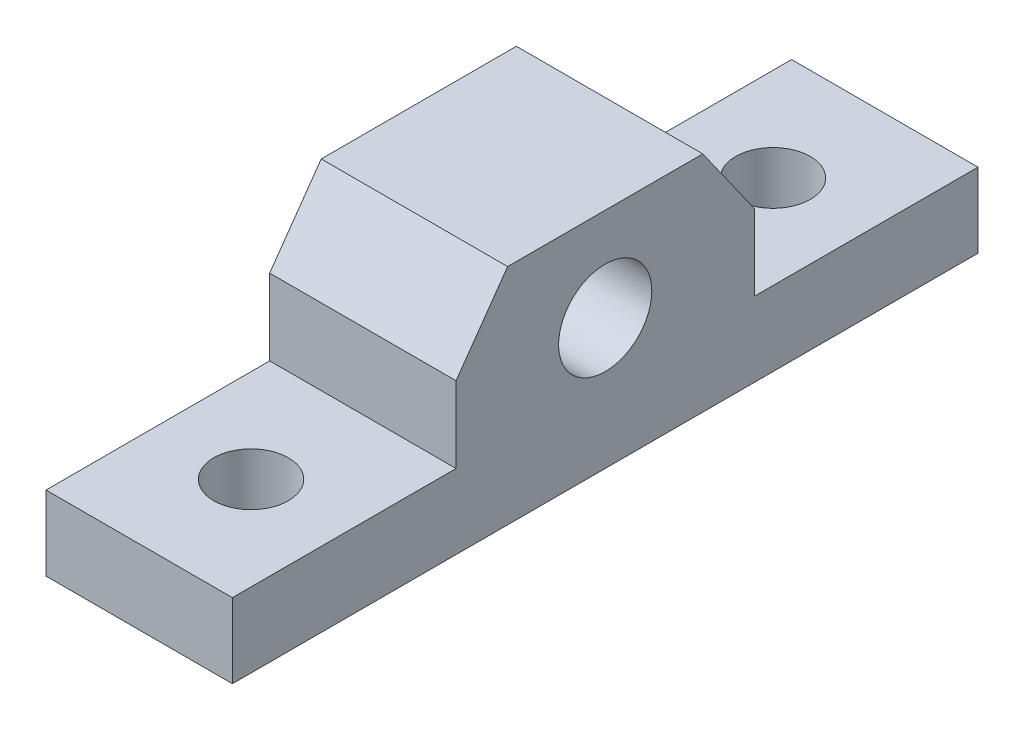
SolidWorks part; units mm, degrees
ref_plane "Спереди" through (0, 0, 0) normal (0, 0, 1) x (1, 0, 0)
ref_plane "Сверху" through (0, 0, 0) normal (0, 1, 0) x (1, 0, 0)
ref_plane "Справа" through (0, 0, 0) normal (1, 0, 0) x (0, 0, -1)
sketch "Эскиз2" plane through (0, 0, 0) normal (1, 0, 0) x (0, 0, -1)
  line L0 (0, 5) -> (40, 5)
  line L1 (0, 5) -> (0, 9)
  line L2 (20, 0) -> (20, 30.2856) construction
  line L3 (0, 9) -> (12, 9)
  line L4 (12, 9) -> (12, 13.0775)
  line L5 (14.7651, 17) -> (25.2349, 17)
  line L6 (12, 13.0775) -> (14.7651, 17)
  line L7 (28, 13.0775) -> (25.2349, 17)
  line L8 (28, 9) -> (28, 13.0775)
  line L9 (40, 9) -> (28, 9)
  line L10 (40, 5) -> (40, 9)
  circle A0 centre (20, 12) radius 2.5
  point P11 (20, 17)
  dimension "D1" = 7
  dimension "D2" = 12
extrude "Вытянуть1" add sketch "Эскиз2" along normal blind 10
sketch "Эскиз3" plane through (0, 9, 0) normal (0, 1, 0) x (1, 0, 0)
  line L0 (5, 0) -> (5, 7.2674) construction
  line L2 (10, 20) -> (23.7765, 20) construction
  line L4 (10, 6) -> (15.9865, 6) construction
  circle A0 centre (5, 6) radius 2
  circle A1 centre (5, 34) radius 2
extrude "Вытянуть2" cut sketch "Эскиз3" against normal through all
